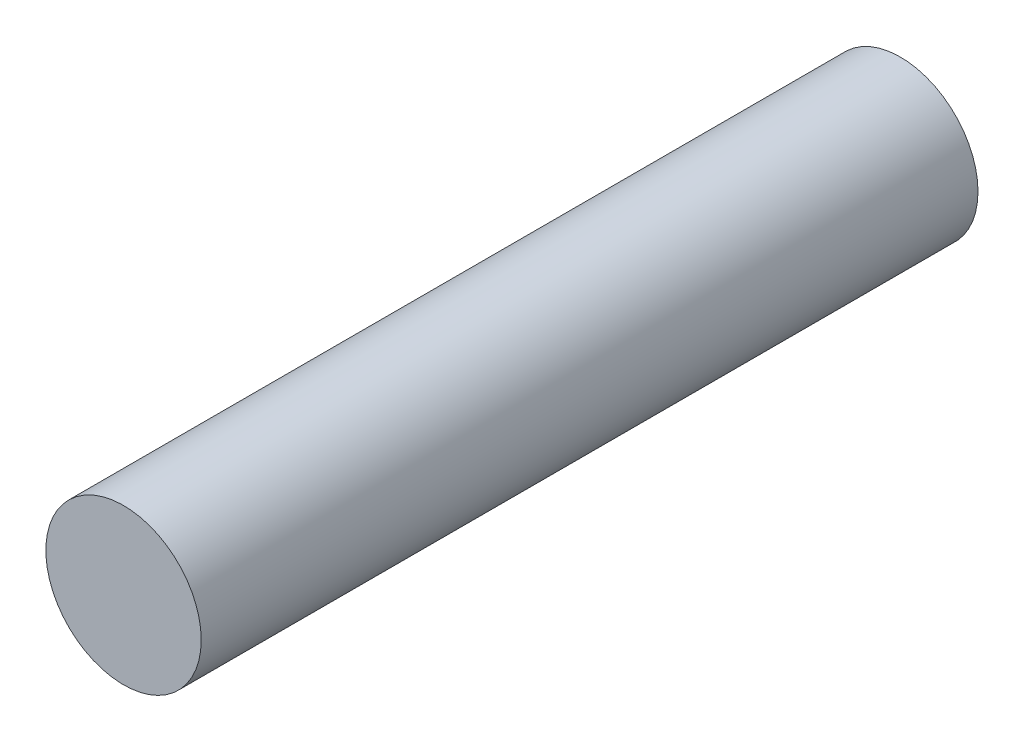
SolidWorks part; units mm, degrees
ref_plane "Plan de face" through (0, 0, 0) normal (0, 0, 1) x (1, 0, 0)
ref_plane "Plan de dessus" through (0, 0, 0) normal (0, 1, 0) x (1, 0, 0)
ref_plane "Plan de droite" through (0, 0, 0) normal (1, 0, 0) x (0, 0, -1)
sketch "Esquisse1" plane through (0, 0, 0) normal (0, 0, 1) x (1, 0, 0)
  circle A0 centre (0, 0) radius 1.5
  dimension "D1" = 3
extrude "Boss.-Extru.1" add sketch "Esquisse1" along normal mid plane 15
